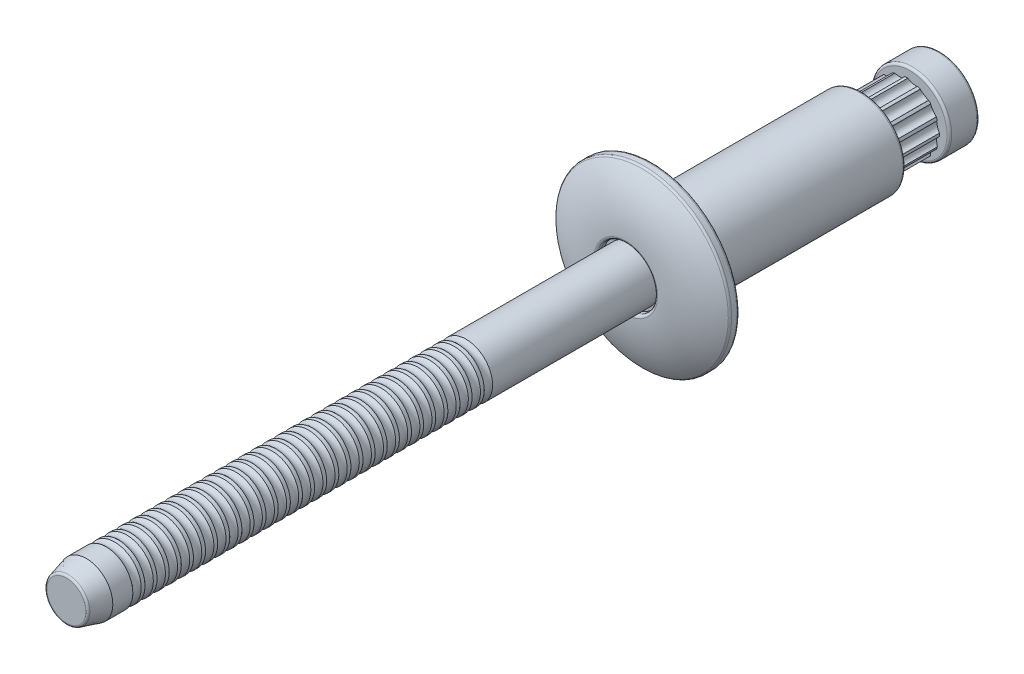
SolidWorks part; units mm, degrees
ref_plane "Front Plane" through (0, 0, 0) normal (0, 0, 1) x (1, 0, 0)
ref_plane "Top Plane" through (0, 0, 0) normal (0, 1, 0) x (1, 0, 0)
ref_plane "Right Plane" through (0, 0, 0) normal (1, 0, 0) x (0, 0, -1)
sketch "Sketch1" plane through (0, 0, 0) normal (1, 0, 0) x (0, 0, -1)
  line L0 (24.0665, 0) -> (-24.0665, 0) construction
  line L1 (19.2913, -2.3813) -> (19.2913, 2.3812) construction
  line L2 (7.8613, -4.7625) -> (7.8613, 4.7625) construction
  line L3 (6.4135, -1.4478) -> (6.4135, 1.4478) construction
  point P4 (0, 0)
  point P9 (19.2913, 0)
  point P12 (7.8613, 0)
  point P15 (6.4135, 0)
  dimension "Diameter" = 4.7625
  dimension "Head Diameter" = 9.525
  dimension "Length" = 11.43
  dimension "Head height" = 1.4478
  dimension "Mandrel Diameter" = 2.8956
  dimension "D1" = 30.48
  dimension "D2" = 4.7752
sketch "Sketch2" plane through (0, 0, 0) normal (1, 0, 0) x (0, 0, -1)
  line L0 (6.4135, -1.7374) -> (6.4135, 1.7374) construction
  line L2 (6.4135, 0) -> (6.7755, 0) construction
  line L3 (24.0665, 0) -> (-24.0665, 0) construction
  line L4 (6.7755, 0) -> (6.7755, 1.5926) construction
  line L5 (6.7755, 1.5926) -> (6.5583, 1.5926)
  line L6 (6.4135, 1.4478) -> (6.4135, 1.7374) construction
  line L7 (6.5583, 1.5926) -> (6.4135, 1.5926) construction
  line L8 (6.4135, 1.4478) -> (6.7755, 1.4478) construction
  line L9 (6.7755, 1.4478) -> (19.2913, 1.4478)
  line L10 (19.2913, -2.3813) -> (19.2913, 2.3812) construction
  line L11 (19.2913, 1.4478) -> (19.2913, 2.3812)
  line L12 (19.2913, 2.3812) -> (7.8613, 2.3812)
  line L13 (7.8613, -4.7625) -> (7.8613, 4.7625) construction
  line L15 (6.7755, 1.5926) -> (6.7755, 1.4478)
  line L16 (-24.0665, 0) -> (24.0665, 0) construction
  line L17 (7.3546, 4.7625) -> (7.8613, 4.7625)
  line L18 (7.8613, 4.7625) -> (7.8613, 2.3812)
  arc A0 (6.4135, 1.7374) -> (7.3546, 4.7625) centre (11.7463, 1.7374) cw
  arc A1 (6.4135, 1.7374) -> (6.5583, 1.5926) centre (6.5583, 1.7374) ccw
  point P4 (6.4135, 0)
  dimension "D1" = 3.4747
  dimension "D2" = 0.3619
  dimension "D3" = 0.5067
revolve "Revolve1" add sketch "Sketch2" angle 360 about L16
fillet "Fillet1" radius 0.1429 3 edges at (0, -4.7625, -7.3546) (0, -4.7625, -7.8613) (0, -2.3812, -19.2913)
chamfer "Chamfer1" distance 0.1448 angle 60 1 edges at (0, -1.4478, -19.2913)
sketch "Sketch3" plane through (0, 0, 0) normal (1, 0, 0) x (0, 0, -1)
  line L0 (-24.0665, -1.1582) -> (-24.0665, 1.1582) construction
  line L1 (21.9177, 2.1431) -> (21.9177, 2.3812) construction
  line L2 (-24.0665, 1.1582) -> (-22.9858, 1.4478)
  line L3 (-22.9858, 1.4478) -> (6.4135, 1.4478)
  line L5 (23.4979, -2.1431) -> (23.4979, 2.1431) construction
  line L6 (21.9177, 2.3812) -> (19.2913, 2.3812) construction
  line L7 (21.9177, 2.1431) -> (23.4979, 2.1431)
  line L8 (23.4979, 2.1431) -> (24.0665, 1.1582)
  line L9 (24.0665, 1.1582) -> (24.0665, 0)
  line L10 (24.0665, 0) -> (-24.0665, 0)
  line L11 (-24.0665, 1.1582) -> (-24.0665, 0)
  line L12 (21.9177, 2.1431) -> (21.9177, 1.4478)
  line L13 (19.2913, 1.4478) -> (6.4135, 1.4478)
  line L14 (21.9177, 1.8097) -> (19.2913, 1.8097) construction
  line L15 (21.9177, 1.4478) -> (21.7087, 1.8097)
  line L16 (21.7087, 1.8097) -> (19.5003, 1.8097)
  line L17 (19.5003, 1.8097) -> (19.2913, 1.4478)
  line L18 (19.2913, 1.4478) -> (21.9177, 1.4478) construction
  line L19 (21.9177, 2.3812) -> (24.0665, 2.3812) construction
  line L20 (24.0665, 2.3812) -> (24.0665, 1.1582) construction
  line L21 (24.0665, -1.1582) -> (24.0665, 1.1582) construction
  line L22 (21.7087, -1.8098) -> (21.7087, 1.8097) construction
  point P4 (-24.0665, 0)
  point P28 (23.4979, 0)
  point P29 (21.7087, 0)
  point P31 (24.0665, 0)
  dimension "D1" = 15
  dimension "D2" = 2.3165
  dimension "D3" = 60
  dimension "D4" = 60
  dimension "D5" = 2.3165
  dimension "D6" = 2.1488
  dimension "D7" = 4.2862
  dimension "D8" = 3.6195
revolve "Revolve2" add sketch "Sketch3" angle 360 about L10
fillet "Fillet2" radius 0.127 3 edges at (0, 2.1431, -23.4979) (0, 2.1431, -21.9177) (0, 1.1582, 24.0665)
sketch "Sketch4" plane through (0, 0, 0) normal (1, 0, 0) x (0, 0, -1)
  line L0 (-24.0665, 0) -> (6.4135, 0) construction
  line L1 (-21.8948, 0) -> (-21.8948, 1.4478) construction
  line L2 (19.2913, 1.4478) -> (-22.9858, 1.4478) construction
  line L3 (-21.8948, 1.4478) -> (-21.4376, 1.4478) construction
  line L4 (-21.4376, 1.4478) -> (-21.4376, 0) construction
  line L5 (-21.6662, 1.4478) -> (-21.6662, 1.3609) construction
  line L6 (-21.6662, -1.3609) -> (-21.6662, 1.3609) construction
  line L7 (-21.8948, 1.4478) -> (-21.8948, 1.7052)
  line L8 (-21.8948, 1.7052) -> (-21.4376, 1.7052)
  line L9 (-21.4376, 1.7052) -> (-21.4376, 1.4478)
  line L10 (-20.7772, 1.7052) -> (-20.7772, 1.4478)
  line L11 (-21.2344, 1.4478) -> (-21.2344, 1.7052)
  line L12 (-21.2344, 1.7052) -> (-20.7772, 1.7052)
  line L13 (-20.1168, 1.7052) -> (-20.1168, 1.4478)
  line L14 (-20.574, 1.4478) -> (-20.574, 1.7052)
  line L15 (-20.574, 1.7052) -> (-20.1168, 1.7052)
  line L16 (-19.4564, 1.7052) -> (-19.4564, 1.4478)
  line L17 (-19.9136, 1.4478) -> (-19.9136, 1.7052)
  line L18 (-19.9136, 1.7052) -> (-19.4564, 1.7052)
  line L19 (-18.796, 1.7052) -> (-18.796, 1.4478)
  line L20 (-19.2532, 1.4478) -> (-19.2532, 1.7052)
  line L21 (-19.2532, 1.7052) -> (-18.796, 1.7052)
  line L22 (-18.1356, 1.7052) -> (-18.1356, 1.4478)
  line L23 (-18.5928, 1.4478) -> (-18.5928, 1.7052)
  line L24 (-18.5928, 1.7052) -> (-18.1356, 1.7052)
  line L25 (-17.4752, 1.7052) -> (-17.4752, 1.4478)
  line L26 (-17.9324, 1.4478) -> (-17.9324, 1.7052)
  line L27 (-17.9324, 1.7052) -> (-17.4752, 1.7052)
  line L28 (-16.8148, 1.7052) -> (-16.8148, 1.4478)
  line L29 (-17.272, 1.4478) -> (-17.272, 1.7052)
  line L30 (-17.272, 1.7052) -> (-16.8148, 1.7052)
  line L31 (-16.1544, 1.7052) -> (-16.1544, 1.4478)
  line L32 (-16.6116, 1.4478) -> (-16.6116, 1.7052)
  line L33 (-16.6116, 1.7052) -> (-16.1544, 1.7052)
  line L34 (-15.494, 1.7052) -> (-15.494, 1.4478)
  line L35 (-15.9512, 1.4478) -> (-15.9512, 1.7052)
  line L36 (-15.9512, 1.7052) -> (-15.494, 1.7052)
  line L37 (-14.8336, 1.7052) -> (-14.8336, 1.4478)
  line L38 (-15.2908, 1.4478) -> (-15.2908, 1.7052)
  line L39 (-15.2908, 1.7052) -> (-14.8336, 1.7052)
  line L40 (-14.1732, 1.7052) -> (-14.1732, 1.4478)
  line L41 (-14.6304, 1.4478) -> (-14.6304, 1.7052)
  line L42 (-14.6304, 1.7052) -> (-14.1732, 1.7052)
  line L43 (-13.5128, 1.7052) -> (-13.5128, 1.4478)
  line L44 (-13.97, 1.4478) -> (-13.97, 1.7052)
  line L45 (-13.97, 1.7052) -> (-13.5128, 1.7052)
  line L46 (-12.8524, 1.7052) -> (-12.8524, 1.4478)
  line L47 (-13.3096, 1.4478) -> (-13.3096, 1.7052)
  line L48 (-13.3096, 1.7052) -> (-12.8524, 1.7052)
  line L49 (-12.192, 1.7052) -> (-12.192, 1.4478)
  line L50 (-12.6492, 1.4478) -> (-12.6492, 1.7052)
  line L51 (-12.6492, 1.7052) -> (-12.192, 1.7052)
  line L52 (-11.5316, 1.7052) -> (-11.5316, 1.4478)
  line L53 (-11.9888, 1.4478) -> (-11.9888, 1.7052)
  line L54 (-11.9888, 1.7052) -> (-11.5316, 1.7052)
  line L55 (-10.8712, 1.7052) -> (-10.8712, 1.4478)
  line L56 (-11.3284, 1.4478) -> (-11.3284, 1.7052)
  line L57 (-11.3284, 1.7052) -> (-10.8712, 1.7052)
  line L58 (-10.2108, 1.7052) -> (-10.2108, 1.4478)
  line L59 (-10.668, 1.4478) -> (-10.668, 1.7052)
  line L60 (-10.668, 1.7052) -> (-10.2108, 1.7052)
  line L61 (-9.5504, 1.7052) -> (-9.5504, 1.4478)
  line L62 (-10.0076, 1.4478) -> (-10.0076, 1.7052)
  line L63 (-10.0076, 1.7052) -> (-9.5504, 1.7052)
  line L64 (-8.89, 1.7052) -> (-8.89, 1.4478)
  line L65 (-9.3472, 1.4478) -> (-9.3472, 1.7052)
  line L66 (-9.3472, 1.7052) -> (-8.89, 1.7052)
  line L67 (-8.2296, 1.7052) -> (-8.2296, 1.4478)
  line L68 (-8.6868, 1.4478) -> (-8.6868, 1.7052)
  line L69 (-8.6868, 1.7052) -> (-8.2296, 1.7052)
  line L70 (-7.5692, 1.7052) -> (-7.5692, 1.4478)
  line L71 (-8.0264, 1.4478) -> (-8.0264, 1.7052)
  line L72 (-8.0264, 1.7052) -> (-7.5692, 1.7052)
  line L73 (-6.9088, 1.7052) -> (-6.9088, 1.4478)
  line L74 (-7.366, 1.4478) -> (-7.366, 1.7052)
  line L75 (-7.366, 1.7052) -> (-6.9088, 1.7052)
  line L76 (-6.2484, 1.7052) -> (-6.2484, 1.4478)
  line L77 (-6.7056, 1.4478) -> (-6.7056, 1.7052)
  line L78 (-6.7056, 1.7052) -> (-6.2484, 1.7052)
  line L79 (-5.588, 1.7052) -> (-5.588, 1.4478)
  line L80 (-6.0452, 1.4478) -> (-6.0452, 1.7052)
  line L81 (-6.0452, 1.7052) -> (-5.588, 1.7052)
  line L82 (-4.9276, 1.7052) -> (-4.9276, 1.4478)
  line L83 (-5.3848, 1.4478) -> (-5.3848, 1.7052)
  line L84 (-5.3848, 1.7052) -> (-4.9276, 1.7052)
  line L85 (-4.2672, 1.7052) -> (-4.2672, 1.4478)
  line L86 (-4.7244, 1.4478) -> (-4.7244, 1.7052)
  line L87 (-4.7244, 1.7052) -> (-4.2672, 1.7052)
  line L88 (-3.6068, 1.7052) -> (-3.6068, 1.4478)
  line L89 (-4.064, 1.4478) -> (-4.064, 1.7052)
  line L90 (-4.064, 1.7052) -> (-3.6068, 1.7052)
  line L91 (-2.9464, 1.7052) -> (-2.9464, 1.4478)
  line L92 (-3.4036, 1.4478) -> (-3.4036, 1.7052)
  line L93 (-3.4036, 1.7052) -> (-2.9464, 1.7052)
  line L94 (-2.286, 1.7052) -> (-2.286, 1.4478)
  line L95 (-2.7432, 1.4478) -> (-2.7432, 1.7052)
  line L96 (-2.7432, 1.7052) -> (-2.286, 1.7052)
  arc A0 (-21.8948, 1.4478) -> (-21.4376, 1.4478) centre (-21.6662, 1.7052) ccw
  arc A1 (-21.2344, 1.4478) -> (-20.7772, 1.4478) centre (-21.0058, 1.7052) ccw
  arc A2 (-20.574, 1.4478) -> (-20.1168, 1.4478) centre (-20.3454, 1.7052) ccw
  arc A3 (-19.9136, 1.4478) -> (-19.4564, 1.4478) centre (-19.685, 1.7052) ccw
  arc A4 (-19.2532, 1.4478) -> (-18.796, 1.4478) centre (-19.0246, 1.7052) ccw
  arc A5 (-18.5928, 1.4478) -> (-18.1356, 1.4478) centre (-18.3642, 1.7052) ccw
  arc A6 (-17.9324, 1.4478) -> (-17.4752, 1.4478) centre (-17.7038, 1.7052) ccw
  arc A7 (-17.272, 1.4478) -> (-16.8148, 1.4478) centre (-17.0434, 1.7052) ccw
  arc A8 (-16.6116, 1.4478) -> (-16.1544, 1.4478) centre (-16.383, 1.7052) ccw
  arc A9 (-15.9512, 1.4478) -> (-15.494, 1.4478) centre (-15.7226, 1.7052) ccw
  arc A10 (-15.2908, 1.4478) -> (-14.8336, 1.4478) centre (-15.0622, 1.7052) ccw
  arc A11 (-14.6304, 1.4478) -> (-14.1732, 1.4478) centre (-14.4018, 1.7052) ccw
  arc A12 (-13.97, 1.4478) -> (-13.5128, 1.4478) centre (-13.7414, 1.7052) ccw
  arc A13 (-13.3096, 1.4478) -> (-12.8524, 1.4478) centre (-13.081, 1.7052) ccw
  arc A14 (-12.6492, 1.4478) -> (-12.192, 1.4478) centre (-12.4206, 1.7052) ccw
  arc A15 (-11.9888, 1.4478) -> (-11.5316, 1.4478) centre (-11.7602, 1.7052) ccw
  arc A16 (-11.3284, 1.4478) -> (-10.8712, 1.4478) centre (-11.0998, 1.7052) ccw
  arc A17 (-10.668, 1.4478) -> (-10.2108, 1.4478) centre (-10.4394, 1.7052) ccw
  arc A18 (-10.0076, 1.4478) -> (-9.5504, 1.4478) centre (-9.779, 1.7052) ccw
  arc A19 (-9.3472, 1.4478) -> (-8.89, 1.4478) centre (-9.1186, 1.7052) ccw
  arc A20 (-8.6868, 1.4478) -> (-8.2296, 1.4478) centre (-8.4582, 1.7052) ccw
  arc A21 (-8.0264, 1.4478) -> (-7.5692, 1.4478) centre (-7.7978, 1.7052) ccw
  arc A22 (-7.366, 1.4478) -> (-6.9088, 1.4478) centre (-7.1374, 1.7052) ccw
  arc A23 (-6.7056, 1.4478) -> (-6.2484, 1.4478) centre (-6.477, 1.7052) ccw
  arc A24 (-6.0452, 1.4478) -> (-5.588, 1.4478) centre (-5.8166, 1.7052) ccw
  arc A25 (-5.3848, 1.4478) -> (-4.9276, 1.4478) centre (-5.1562, 1.7052) ccw
  arc A26 (-4.7244, 1.4478) -> (-4.2672, 1.4478) centre (-4.4958, 1.7052) ccw
  arc A27 (-4.064, 1.4478) -> (-3.6068, 1.4478) centre (-3.8354, 1.7052) ccw
  arc A28 (-3.4036, 1.4478) -> (-2.9464, 1.4478) centre (-3.175, 1.7052) ccw
  arc A29 (-2.7432, 1.4478) -> (-2.286, 1.4478) centre (-2.5146, 1.7052) ccw
  point P4 (-21.8948, 0)
  point P16 (-21.6662, 0)
  dimension "D1" = 2.1717
  dimension "D2" = 0.4572
  dimension "D3" = 2.7219
  dimension "D5" = 0.2032
  dimension "D4" = 30
revolve "Cut-Revolve1" cut sketch "Sketch4" angle 360 about L0
sketch "Sketch5" plane through (0, 0, -21.9177) normal (0, 0, 1) x (1, 0, 0)
  line L0 (0, 1.8097) -> (0, 0) construction
  line L1 (0, 0) -> (-0.305, 1.5336) construction
  line L2 (0, 0) -> (-0.6926, 1.672) construction
  line L3 (0, -1.1582) -> (0, 1.1582) construction
  line L4 (-0.305, 1.5336) -> (-0.3596, 1.808) construction
  line L6 (-0.0798, 1.808) -> (-0.0798, 2.3812) construction
  circle A0 centre (0, 0) radius 1.8097 construction
  circle A1 centre (0, 0) radius 1.4478 construction
  arc A2 (-0.0798, 1.808) -> (-0.6181, 1.7009) centre (-0.3596, 1.808) cw
  circle A3 centre (0, 0) radius 1.5636 construction
  arc A4 (-0.0798, 1.808) -> (-0.6181, 1.7009) centre (0, 0) ccw
  dimension "D3" = 3.1272
  dimension "D1" = 22.5
  dimension "D2" = 11.25
extrude "Cut-Extrude1" cut sketch "Sketch5" along normal through all
pattern_circular "CirPattern1" count 16 over 360 about axis through (0, 0, 0) along (0, 0, 1) of "Cut-Extrude1"
fillet "Fillet3" radius 0.1905 1 edges at (0, -2.3812, -7.8613)
sketch "Sketch6" plane through (0, 0, 0) normal (0, 0, 1) x (1, 0, 0)
  line L0 (-2.3813, 0) -> (2.3813, 0) construction
  line L1 (-4.7625, 0) -> (4.7625, 0) construction
  point P4 (0, 0)
  point P6 (-2.3813, 0)
  point P7 (2.3813, 0)
  point P10 (0, 0)
  point P11 (-4.7625, 0)
  point P12 (4.7625, 0)
  dimension "D1" = 4.7625
  dimension "D2" = 9.525
sketch "Sketch7" plane through (0, 0, 0) normal (1, 0, 0) x (0, 0, -1)
  point P0 (-24.0665, 1.1582)
  point P1 (7.8613, -4.7625)
  point P3 (19.2913, -2.3813)
  point P6 (6.4135, 1.4478)
  point P8 (7.8613, 4.7625)
equation "\"D1@Sketch2\" = \"Mandrel Diameter@Sketch1\" * 1.2"
equation "\"D2@Sketch2\"=\"Head Height@sketch1\"*.25"
equation "\"D3@Sketch2\" = \"Head height@Sketch1\" * .35"
equation "\"D1@Fillet1\"=\"Diameter@Sketch1\" * .03"
equation "\"D1@Chamfer1\"=\"Mandrel Diameter@Sketch1\" * .05"
equation "\"D2@Sketch3\"=\"Mandrel Diameter@sketch1\"*.8"
equation "\"D5@Sketch3\" = \"Mandrel Diameter@Sketch1\" * .8"
equation "\"D6@Sketch3\" = \"D2@Sketch1\" * .45"
equation "\"D7@Sketch3\"=\"Diameter@sketch1\"*.9"
equation "\"D8@Sketch3\"=\"Mandrel Diameter@Sketch1\" * 1.25"
equation "\"D1@Sketch4\"=\"Mandrel Diameter@Sketch1\"*.75"
equation "\"D2@Sketch4\"=\"D1@Sketch1\" * .015"
equation "\"D3@Sketch4\"=\"Mandrel Diameter@Sketch1\" * .94"
equation "\"D3@Sketch5\"=\"Mandrel Diameter@Sketch1\" * 1.08"
equation "\"D1@Fillet3\" = \"Diameter@Sketch1\" * .04"
equation "\"D1@Sketch6\"=\"Diameter@sketch1\""
equation "\"D2@Sketch6\"=\"Head Diameter@sketch1\""
